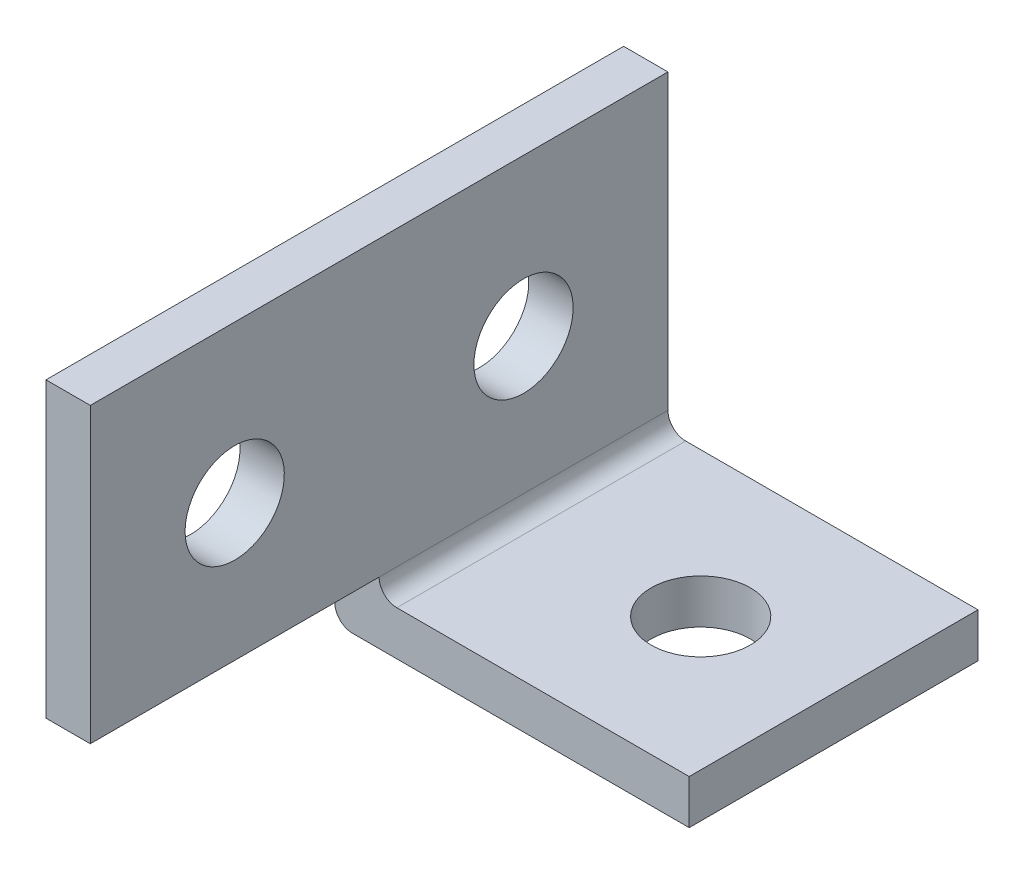
SolidWorks part; units mm, degrees
ref_plane "前视基准面" through (0, 0, 0) normal (0, 0, 1) x (1, 0, 0)
ref_plane "上视基准面" through (0, 0, 0) normal (0, 1, 0) x (1, 0, 0)
ref_plane "右视基准面" through (0, 0, 0) normal (1, 0, 0) x (0, 0, -1)
sketch "草图1" plane through (0, 0, 0) normal (0, 0, 1) x (1, 0, 0)
  line L0 (2.54, 0) -> (50.8, 0)
  line L1 (50.8, 0) -> (50.8, 6.35)
  line L2 (50.8, 6.35) -> (8.89, 6.35)
  line L3 (0, 2.54) -> (0, 50.901)
  line L4 (0, 50.901) -> (6.35, 50.901)
  line L5 (6.35, 50.901) -> (6.35, 8.89)
  arc A0 (6.35, 8.89) -> (8.89, 6.35) centre (8.89, 8.89) ccw
  arc A1 (0, 2.54) -> (2.54, 0) centre (2.54, 2.54) ccw
  point P11 (0, 0)
  dimension "D1" = 2.54
  dimension "D2" = 2.54
extrude "凸台-拉伸1" add sketch "草图1" along normal blind 41.402
ref_plane "基准面1" through (0, 0, 0) normal (0, -1, 0) x (-1, 0, 0)
sketch "草图3" plane through (0, 0, 0) normal (0, -1, 0) x (-1, 0, 0)
  line L0 (0, -20.701) -> (-31.75, -20.701) construction
  line L1 (0, -41.402) -> (0, 0) construction
  circle A0 centre (-31.75, -20.701) radius 7.112
ref_plane "基准面2" through (0, 0, 0) normal (-1, 0, 0) x (0, 0, 1)
sketch "草图4" plane through (0, 0, 0) normal (-1, 0, 0) x (0, 0, 1)
  line L0 (20.701, 0) -> (20.701, 28.448) construction
  line L1 (13.589, 0) -> (27.813, 0) construction
  circle A0 centre (20.701, 28.448) radius 7.112
extrude "切除-拉伸1" cut sketch "草图4" against normal through all
extrude "切除-拉伸2" cut sketch "草图3" against normal through all contours A0
sketch "Sketch1" plane through (0, 0, 0) normal (-1, 0, 0) x (0, 0, 1)
  line L0 (41.402, 50.901) -> (82.804, 50.901)
  line L1 (82.804, 50.901) -> (82.804, 8.89)
  line L2 (82.804, 8.89) -> (41.402, 8.89)
  line L3 (41.402, 8.89) -> (41.402, 50.901)
extrude "Boss-Extrude1" add sketch "Sketch1" against normal blind 6.35
sketch "Sketch3" plane through (0, 0, 0) normal (-1, 0, 0) x (0, 0, 1)
  line L0 (41.402, 8.89) -> (41.402, 50.901) construction
  line L1 (82.804, 50.901) -> (0, 50.901) construction
  circle A0 centre (20.701, 28.448) radius 7.112
  circle A1 centre (62.103, 28.448) radius 7.112
extrude "Cut-Extrude1" cut sketch "Sketch3" against normal through all
